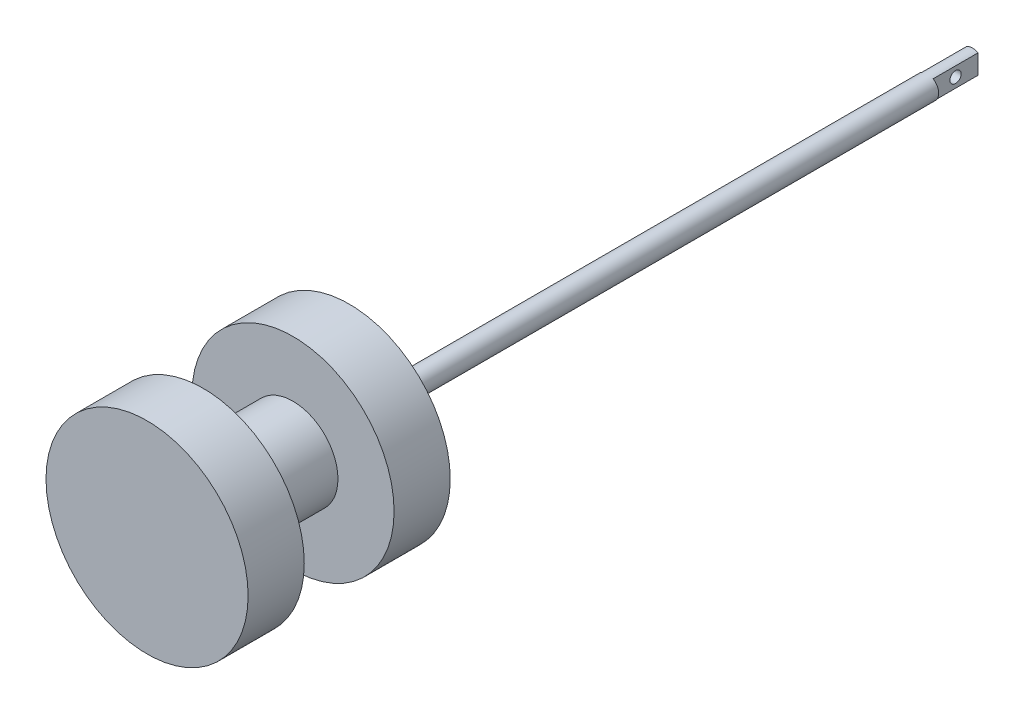
SolidWorks part; units mm, degrees
ref_plane "Front Plane" through (0, 0, 0) normal (0, 0, 1) x (1, 0, 0)
ref_plane "Top Plane" through (0, 0, 0) normal (0, 1, 0) x (1, 0, 0)
ref_plane "Right Plane" through (0, 0, 0) normal (1, 0, 0) x (0, 0, -1)
sketch "Sketch1" plane through (0, 0, 0) normal (1, 0, 0) x (0, 0, -1)
  line L0 (0, 0) -> (1837.5, 0)
  line L1 (1837.5, 0) -> (1837.5, -25)
  line L2 (1837.5, -25) -> (450, -25)
  line L3 (450, -25) -> (450, -225)
  line L4 (450, -225) -> (325, -225)
  line L5 (325, -225) -> (325, -100)
  line L6 (325, -100) -> (125, -100)
  line L7 (125, -100) -> (125, -225)
  line L8 (125, -225) -> (0, -225)
  line L9 (0, -225) -> (0, 0)
  dimension "D1" = 225
  dimension "D2" = 125
  dimension "D3" = 200
  dimension "D4" = 125
  dimension "D5" = 100
  dimension "D6" = 1387.5
  dimension "D7" = 25
revolve "Revolve1" add sketch "Sketch1" angle 360 about L0
sketch "Sketch2" plane through (0, 0, -1837.5) normal (0, 0, -1) x (-1, 0, 0)
  line L1 (-12.5, 34.2994) -> (-44.5503, 34.2994)
  line L2 (-12.5, 34.2994) -> (-12.5, -31.1766)
  line L3 (-12.5, -31.1766) -> (-44.5503, -31.1766)
  line L4 (-44.5503, 34.2994) -> (-44.5503, -31.1766)
  line L5 (12.5, 35.9783) -> (37.0968, 35.9783)
  line L6 (12.5, 35.9783) -> (12.5, -31.5124)
  line L7 (12.5, -31.5124) -> (37.0968, -31.5124)
  line L8 (37.0968, 35.9783) -> (37.0968, -31.5124)
  dimension "D1" = 12.5
  dimension "D2" = 25
extrude "Cut-Extrude1" cut sketch "Sketch2" against normal blind 100
sketch "Sketch3" plane through (12.5, 0, 0) normal (1, 0, 0) x (0, 0, -1)
  line L2 (1737.5, -21.6506) -> (1837.5, 21.6506) construction
  line L3 (1837.5, -21.6506) -> (1737.5, 21.6506) construction
  circle A0 centre (1787.5, 0) radius 12.5
  dimension "D1" = 25
extrude "Cut-Extrude2" cut sketch "Sketch3" against normal up to next
